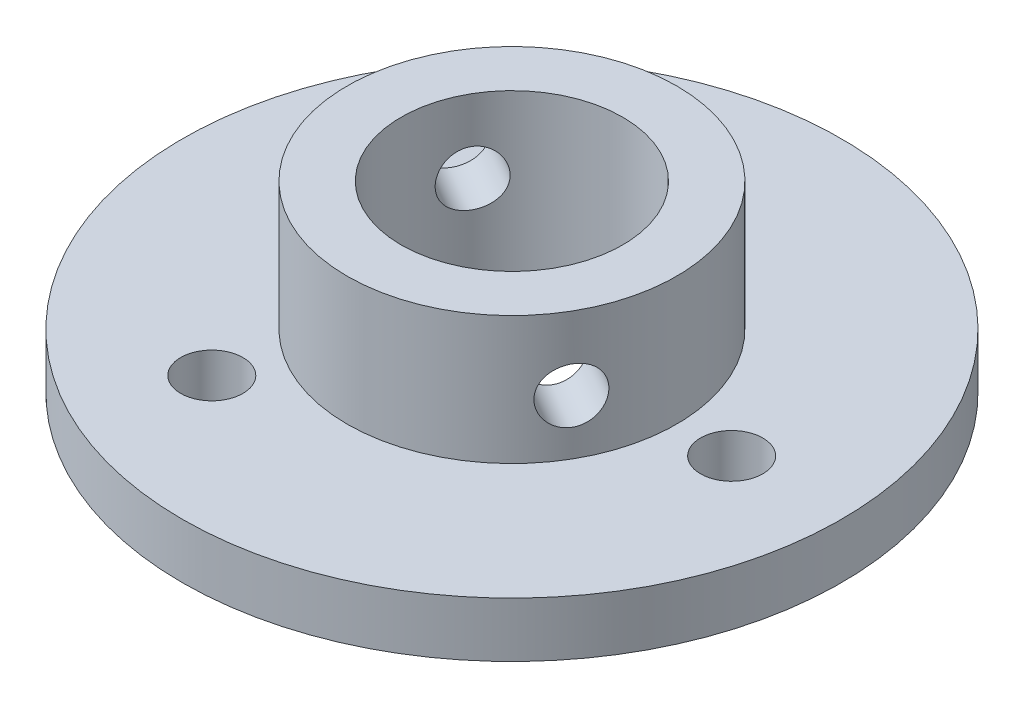
SolidWorks part; units mm, degrees
other "Metal Wheel Hub"
other "Metal Wheel Hub Left"
ref_plane "Front Plane" through (0, 0, 0) normal (0, 0, 1) x (1, 0, 0)
ref_plane "Top Plane" through (0, 0, 0) normal (0, 1, 0) x (1, 0, 0)
ref_plane "Right Plane" through (0, 0, 0) normal (1, 0, 0) x (0, 0, -1)
sketch3d "Hub neck sketch datum points"
  point P0 (-19.0092, -273, -53.2449)
  point P1 (-9.0092, -273, -53.2449)
  point P2 (-19.0092, -273, -63.2449)
ref_plane "Hub neck sketch plane" through (0, -273, 0) normal (0, 1, 0) x (1, 0, 0)
sketch "Hub neck sketch" plane through (0, -273, 0) normal (0, 1, 0) x (1, 0, 0)
  circle A0 centre (-19.0092, 53.2449) radius 9
extrude "Hub neck" add sketch "Hub neck sketch" along normal blind 10 separate body
sketch3d "Rim clamp flange sketch datum points"
  point P0 (-19.0092, -266, -53.2449)
  point P1 (-9.0092, -266, -53.2449)
  point P2 (-19.0092, -266, -63.2449)
ref_plane "Rim clamp flange sketch plane" through (0, -266, 0) normal (0, 1, 0) x (1, 0, 0)
sketch "Rim clamp flange sketch" plane through (0, -266, 0) normal (0, 1, 0) x (1, 0, 0)
  circle A0 centre (-19.0092, 53.2449) radius 18
extrude "Rim clamp flange" add sketch "Rim clamp flange sketch" along normal blind 3
sketch3d "Axle clearance sketch datum points"
  point P0 (-19.0092, -273.1, -53.2449)
  point P1 (-9.0092, -273.1, -53.2449)
  point P2 (-19.0092, -273.1, -63.2449)
ref_plane "Axle clearance sketch plane" through (0, -273.1, 0) normal (0, 1, 0) x (1, 0, 0)
sketch "Axle clearance sketch" plane through (0, -273.1, 0) normal (0, 1, 0) x (1, 0, 0)
  circle A0 centre (-19.0092, 53.2449) radius 6.05
extrude "Axle clearance" cut sketch "Axle clearance sketch" along normal blind 10.2
sketch3d "Rim bolt clearance pattern sketch datum points"
  point P0 (-19.0092, -266.1, -53.2449)
  point P1 (-9.0092, -266.1, -53.2449)
  point P2 (-19.0092, -266.1, -63.2449)
ref_plane "Rim bolt clearance pattern sketch plane" through (0, -266.1, 0) normal (0, 1, 0) x (1, 0, 0)
sketch "Rim bolt clearance pattern sketch" plane through (0, -266.1, 0) normal (0, 1, 0) x (1, 0, 0)
  circle A0 centre (-7.0092, 53.2449) radius 1.7
  circle A1 centre (-25.0092, 42.8526) radius 1.7
  circle A2 centre (-25.0092, 63.6372) radius 1.7
extrude "Rim bolt clearance pattern" cut sketch "Rim bolt clearance pattern sketch" along normal blind 3.2
sketch3d "Positive hub pin bore sketch datum points"
  point P0 (-27.6694, -269, -58.2449)
  point P1 (-22.6694, -269, -66.9051)
  point P2 (-27.6694, -259, -58.2449)
ref_plane "Positive hub pin bore sketch plane" through (-45.9729, 0, -26.5424) normal (0.866, 0, 0.5) x (0.5, 0, -0.866)
sketch "Positive hub pin bore sketch" plane through (-45.9729, 0, -26.5424) normal (0.866, 0, 0.5) x (0.5, 0, -0.866)
  circle A0 centre (36.6068, -269) radius 1.5
extrude "Positive hub pin bore" cut sketch "Positive hub pin bore sketch" along normal blind 20
sketch3d "Mirror1 profile datum points"
  point P0 (0, 0, 0)
  point P1 (10, 0, 0)
  point P2 (0, 0, 10)
ref_plane "Mirror1 profile plane" through (0, 0, 0) normal (0, -1, 0) x (-1, 0, 0)
mirror "Mirror1" about plane through (0, 0, 0) normal (0, -1, 0) of bodies 105
delete or keep bodies "Remove1" type delete bodies bodies 105
